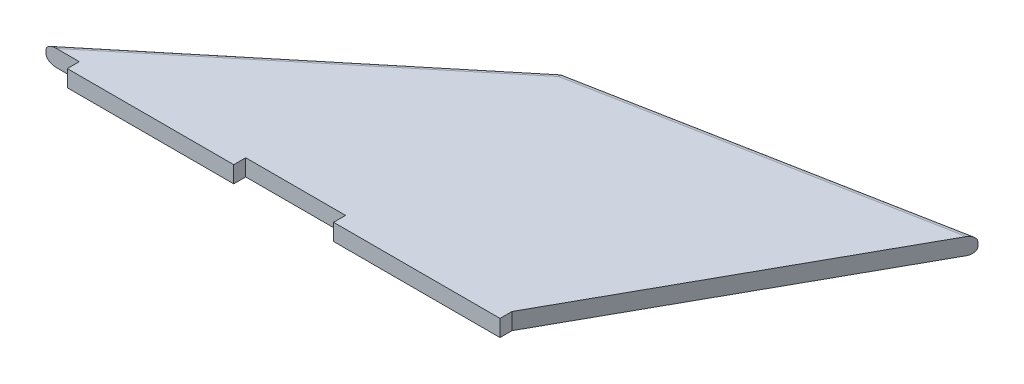
SolidWorks part; units mm, degrees
ref_plane "Front Plane" through (0, 0, 0) normal (0, 0, 1) x (1, 0, 0)
ref_plane "Top Plane" through (0, 0, 0) normal (0, 1, 0) x (1, 0, 0)
ref_plane "Right Plane" through (0, 0, 0) normal (1, 0, 0) x (0, 0, -1)
sketch "Sketch1" plane through (0, 0, 0) normal (0, 1, 0) x (1, 0, 0)
  line L0 (0, 0) -> (42.5, 35)
  line L1 (42.5, 35) -> (95, 45)
  line L2 (95, 45) -> (70, 0)
  line L3 (45, 0) -> (30, 0)
  line L4 (5, 0) -> (0, 0)
  line L6 (5, 0) -> (5, -1.8)
  line L7 (5, -1.8) -> (30, -1.8)
  line L8 (30, 0) -> (30, -1.8)
  line L10 (45, 0) -> (45, -1.8)
  line L11 (45, -1.8) -> (70, -1.8)
  line L12 (70, 0) -> (70, -1.8)
  dimension "D1" = 70
  dimension "D2" = 95
  dimension "D3" = 45
  dimension "D4" = 35
  dimension "D5" = 42.5
  dimension "D6" = 1.8
  dimension "D7" = 15
  dimension "D8" = 25
  dimension "D9" = 5
extrude "Boss-Extrude1" add sketch "Sketch1" along normal blind 2.5
fillet "Fillet1" radius 1 5 edges at (42.5, 1.25, -35) (21.25, 2.5, -17.5) (21.25, 0, -17.5) (68.75, 0, -40) (68.75, 2.5, -40)
